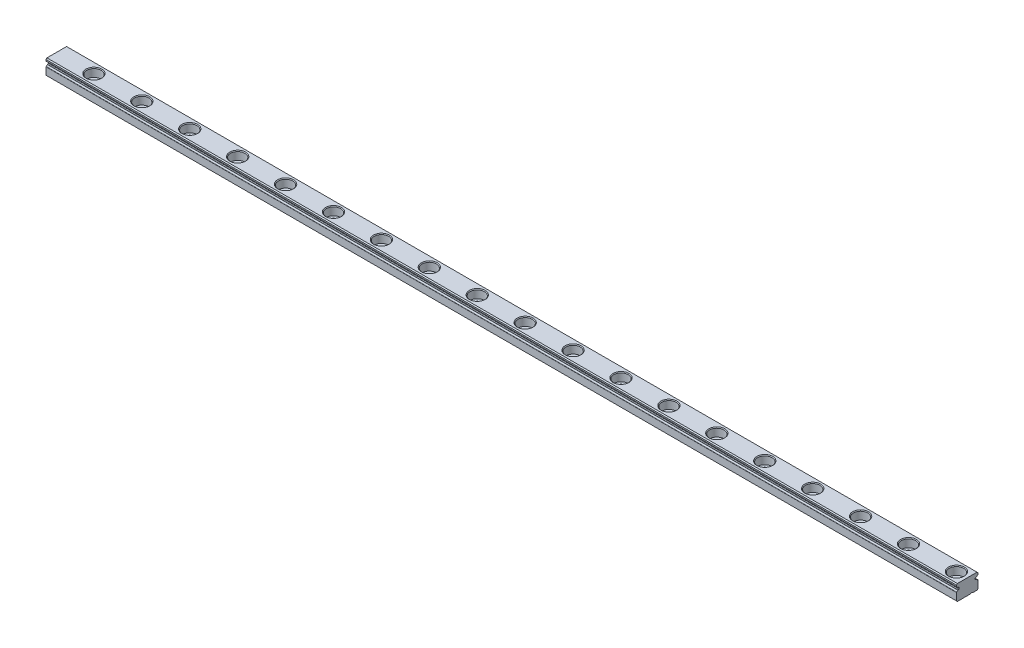
SolidWorks part; units mm, degrees
ref_plane "前视基准面" through (0, 0, 0) normal (0, 0, 1) x (1, 0, 0)
ref_plane "上视基准面" through (0, 0, 0) normal (0, 1, 0) x (1, 0, 0)
ref_plane "右视基准面" through (0, 0, 0) normal (1, 0, 0) x (0, 0, -1)
ref_plane "基准面4" through (0, 0, 0) normal (1, 0, 0) x (0, 0, -1)
sketch "草图1" plane through (0, 0, 0) normal (1, 0, 0) x (0, 0, -1)
  line L0 (-4.5, 6.1) -> (-4.5, 5.5583)
  line L1 (-3.8438, 4.9397) -> (-3.4666, 4.8536)
  line L2 (-3.35, 4.7074) -> (-3.35, 4.2926)
  line L3 (-3.4666, 4.1464) -> (-3.8438, 4.0603)
  line L4 (-4.5, 3.4417) -> (-4.5, 0.4)
  line L5 (-4.5, 0.4) -> (-4.1, 0)
  line L6 (-4.1, 0) -> (1.4, 0)
  line L7 (2.2, 0) -> (4.1, 0)
  line L8 (4.1, 0) -> (4.5, 0.4)
  line L9 (4.5, 0.4) -> (4.5, 3.4417)
  line L10 (3.8438, 4.0603) -> (3.4666, 4.1464)
  line L11 (3.35, 4.2926) -> (3.35, 4.7074)
  line L12 (3.4666, 4.8536) -> (3.8438, 4.9397)
  line L13 (4.5, 5.5583) -> (4.5, 6.1)
  line L14 (4.5, 6.1) -> (4.1, 6.5)
  line L15 (4.1, 6.5) -> (-4.1, 6.5)
  line L16 (-4.1, 6.5) -> (-4.5, 6.1)
  arc A0 (-4.5, 5.5583) -> (-4.4084, 5.4201) centre (-4.35, 5.5583) ccw
  arc A1 (-4.4084, 5.4201) -> (-3.9395, 5.0095) centre (-4.8, 4.5) cw
  arc A2 (-3.9395, 5.0095) -> (-3.8438, 4.9397) centre (-3.8104, 5.0859) ccw
  arc A3 (-3.4666, 4.8536) -> (-3.35, 4.7074) centre (-3.5, 4.7074) cw
  arc A4 (-3.35, 4.2926) -> (-3.4666, 4.1464) centre (-3.5, 4.2926) cw
  arc A5 (-3.8438, 4.0603) -> (-3.9395, 3.9905) centre (-3.8104, 3.9141) ccw
  arc A6 (-3.9395, 3.9905) -> (-4.4084, 3.5799) centre (-4.8, 4.5) cw
  arc A7 (-4.4084, 3.5799) -> (-4.5, 3.4417) centre (-4.35, 3.4417) ccw
  arc A8 (1.4, 0) -> (2.2, 0) centre (1.8, -0.3) cw
  arc A9 (4.5, 3.4417) -> (4.4084, 3.5799) centre (4.35, 3.4417) ccw
  arc A10 (4.4084, 3.5799) -> (3.9395, 3.9905) centre (4.8, 4.5) cw
  arc A11 (3.9395, 3.9905) -> (3.8438, 4.0603) centre (3.8104, 3.9141) ccw
  arc A12 (3.4666, 4.1464) -> (3.35, 4.2926) centre (3.5, 4.2926) cw
  arc A13 (3.35, 4.7074) -> (3.4666, 4.8536) centre (3.5, 4.7074) cw
  arc A14 (3.8438, 4.9397) -> (3.9395, 5.0095) centre (3.8104, 5.0859) ccw
  arc A15 (3.9395, 5.0095) -> (4.4084, 5.4201) centre (4.8, 4.5) cw
  arc A16 (4.4084, 5.4201) -> (4.5, 5.5583) centre (4.35, 5.5583) ccw
extrude "凸台-拉伸1" add sketch "草图1" against normal mid plane 380
ref_plane "基准面5" through (0, 0, 0) normal (0, 0, 1) x (1, 0, 0)
sketch "草图2" plane through (0, 0, 0) normal (0, 0, 1) x (1, 0, 0)
  line L0 (-14.5, 6.5) -> (-11.2, 6.5)
  line L1 (-11.2, 6.5) -> (-11.5, 6.2)
  line L2 (-11.5, 6.2) -> (-11.5, 3)
  line L3 (-11.5, 3) -> (-12.75, 3)
  line L4 (-12.75, 3) -> (-12.75, 0.3)
  line L5 (-12.75, 0.3) -> (-12.45, 0)
  line L6 (-12.45, 0) -> (-14.5, 0)
  line L7 (-14.5, 0) -> (-14.5, 6.5)
  line L8 (-14.5, 0) -> (-14.5, 6.5) construction
revolve "切除-旋转1" cut sketch "草图2" angle 360 about L8
pattern_linear "阵列(线性)1" count 11 spacing 20 along (1, 0, 0) count 9 spacing 20 along (-1, 0, 0) of "切除-旋转1"
